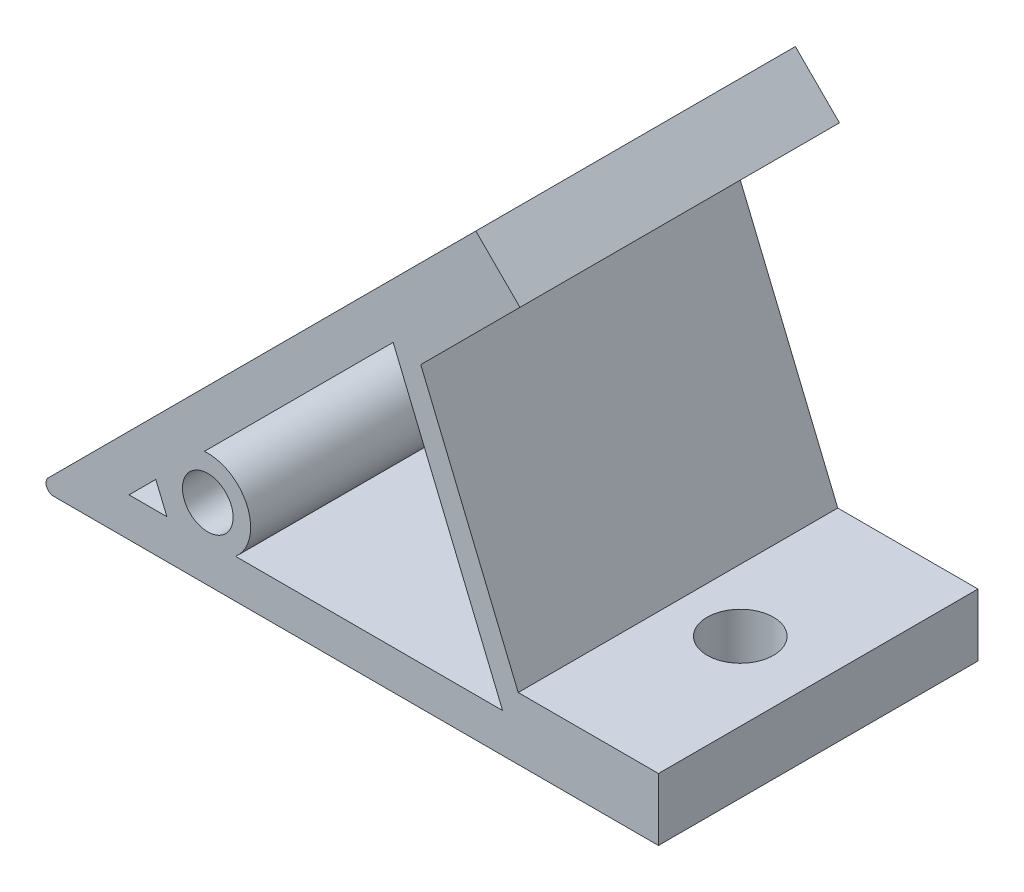
SolidWorks part; units mm, degrees
ref_plane "前视基准面" through (0, 0, 0) normal (0, 0, 1) x (1, 0, 0)
ref_plane "上视基准面" through (0, 0, 0) normal (0, 1, 0) x (1, 0, 0)
ref_plane "右视基准面" through (0, 0, 0) normal (1, 0, 0) x (0, 0, -1)
sketch "草图1" plane through (0, 0, 0) normal (0, 0, 1) x (1, 0, 0)
  line B0 (-77.5858, 0) -> (0, 0)
  line B1 (-67.9289, 5) -> (-63.0745, 5)
  line B2 (-54.2575, 5) -> (-20, 5)
  line B3 (-17.9955, 8) -> (0, 8)
  line B4 (-78.2929, 1.7071) -> (-23.4315, 56.5685)
  line B5 (-67.9289, 5) -> (-64.4963, 8.4326)
  line B6 (-58.2617, 14.6672) -> (-34.0381, 38.8909)
  line B7 (-30.4993, 38.187) -> (-17.7746, 50.9117)
  line B8 (0, 0) -> (0, 8)
  line B9 (-17.7746, 50.9117) -> (-23.4315, 56.5685)
  line B10 (-20, 5) -> (-34.0381, 38.8909)
  line B11 (-17.9955, 8) -> (-30.4993, 38.187)
  line B12 (-63.0745, 5) -> (-64.4963, 8.4326)
  arc B13 (-78.2929, 1.7071) -> (-77.5858, 0) centre (-77.5858, 1) ccw
  circle B14 centre (-57.8269, 9.1844) radius 3.25
  arc B15 (-54.2575, 5) -> (-58.2617, 14.6672) centre (-57.8269, 9.1844) ccw
sketch_block_instance "A$C18907C9D-1"
sketch_block "A$C18907C9D"
extrude "凸台-拉伸1" add sketch "草图1" along normal mid plane 41
sketch "草图3" plane through (0, 8, 0) normal (0, 1, 0) x (1, 0, 0)
  line L0 (0, -20.5) -> (0, 20.5) construction
  circle A0 centre (-10, 0) radius 4.25
  dimension "D1" = 10
extrude "切除-拉伸1" cut sketch "草图3" against normal blind 17
sketch "草图4" plane through (-12.5317, -5.1908, 0) normal (0.9239, 0.3827, 0) x (0, 0, -1)
  line L0 (-20.5, 30.6147) -> (20.5, 30.6147) construction
  line L1 (-20.5, 14.2776) -> (-20.5, 46.9517) construction
  line L2 (20.5, 14.2776) -> (20.5, 46.9517) construction
ref_plane "基准面2" through (-11.7157, 28.2843, 0) normal (-0.3827, 0.9239, 0) x (0.9239, 0.3827, 0)
mirror "镜向1" about plane through (-11.7157, 28.2843, 0) normal (-0.3827, 0.9239, 0) of "切除-拉伸1"
